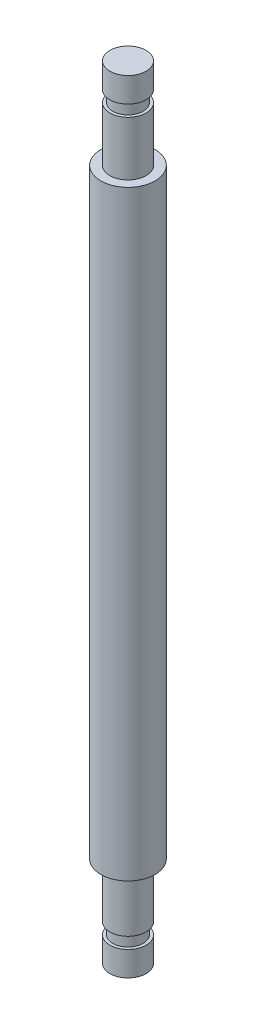
SolidWorks part; units mm, degrees
ref_plane "Front Plane" through (0, 0, 0) normal (0, 0, 1) x (1, 0, 0)
ref_plane "Top Plane" through (0, 0, 0) normal (0, 1, 0) x (1, 0, 0)
ref_plane "Right Plane" through (0, 0, 0) normal (1, 0, 0) x (0, 0, -1)
sketch "Sketch1" plane through (0, 0, 0) normal (0, 1, 0) x (1, 0, 0)
  circle A0 centre (0, 0) radius 3.175
  dimension "D1" = 6.35
extrude "Boss-Extrude1" add sketch "Sketch1" along normal blind 137.2
sketch "Sketch2" plane through (0, 137.2, 0) normal (0, 1, 0) x (1, 0, 0)
  circle A0 centre (0, 0) radius 4.7625
  dimension "D1" = 9.525
extrude "Boss-Extrude2" add sketch "Sketch2" against normal blind 105.45 from offset 15.88 offset against normal yes
sketch "Sketch4" plane through (0, 121.32, 0) normal (0, 1, 0) x (1, 0, 0)
  circle A0 centre (0, 0) radius 2.665
  circle A1 centre (0, 0) radius 3.175
  dimension "D1" = 5.33
extrude "Cut-Extrude1" cut sketch "Sketch4" along normal blind 2 from offset 9.53
sketch "Sketch5" plane through (0, 0, 0) normal (0, 0, 1) x (1, 0, 0)
  line L0 (-4.7625, 68.595) -> (8.6362, 68.595) construction
  line L1 (-4.7625, 121.32) -> (-4.7625, 15.87) construction
ref_plane "Plane1" through (0, 68.595, 0) normal (0, 1, 0) x (1, 0, 0)
mirror "Mirror1" about plane through (0, 68.595, 0) normal (0, 1, 0) of "Cut-Extrude1"
